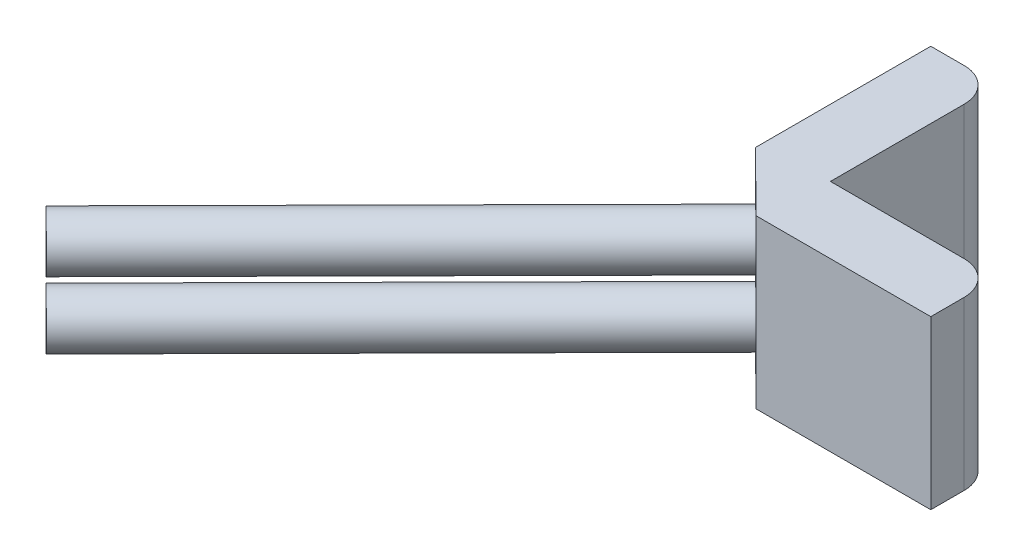
SolidWorks part; units mm, degrees
ref_plane "Front Plane" through (0, 0, 0) normal (0, 0, 1) x (1, 0, 0)
ref_plane "Top Plane" through (0, 0, 0) normal (0, 1, 0) x (1, 0, 0)
ref_plane "Right Plane" through (0, 0, 0) normal (1, 0, 0) x (0, 0, -1)
sketch "Sketch1" plane through (0, 0, 0) normal (0, 1, 0) x (1, 0, 0)
  line L0 (0, 0) -> (0, 70)
  line L1 (0, 70) -> (20, 70)
  line L2 (20, 70) -> (20, 20)
  line L3 (20, 20) -> (70, 20)
  line L4 (70, 20) -> (70, 0)
  line L5 (70, 0) -> (0, 0)
  dimension "D1" = 20
  dimension "D2" = 20
  dimension "D3" = 50
  dimension "D4" = 50
extrude "Boss-Extrude1" add sketch "Sketch1" along normal blind 50
sketch "Sketch2" plane through (0, 50, 0) normal (0, 1, 0) x (1, 0, 0)
  line L0 (0, 17.6) -> (17.755, 0)
  line L1 (0, 70) -> (0, 0) construction
  line L2 (0, 0) -> (70, 0) construction
  line L3 (0, 17.6) -> (0, 0)
  line L4 (0, 0) -> (17.755, 0)
  dimension "D1" = 25
  dimension "D2" = 17.6
extrude "Cut-Extrude1" cut sketch "Sketch2" against normal blind 50
sketch "Sketch3" plane through (8.7997, 0, -8.8772) normal (-0.704, 0, 0.7102) x (0.7102, 0, 0.704)
  line L0 (12.6096, 0) -> (12.6096, 50) construction
  line L1 (12.6096, 0) -> (-12.3904, 0) construction
  line L2 (0.1096, 50) -> (0, 0) construction
  circle A0 centre (0.1096, 35) radius 7.5
  circle A1 centre (0.1096, 15) radius 7.5
  point P8 (0, 0)
  dimension "D1" = 15
  dimension "D2" = 15
  dimension "D3" = 12.5
  dimension "D4" = 12.5
  dimension "D5" = 20
  dimension "D6" = 15
extrude "Boss-Extrude2" add sketch "Sketch3" along normal blind 150 contours A0 | A1
fillet "Fillet1" radius 10 2 edges at (20, 25, -70) (70, 25, -20)
